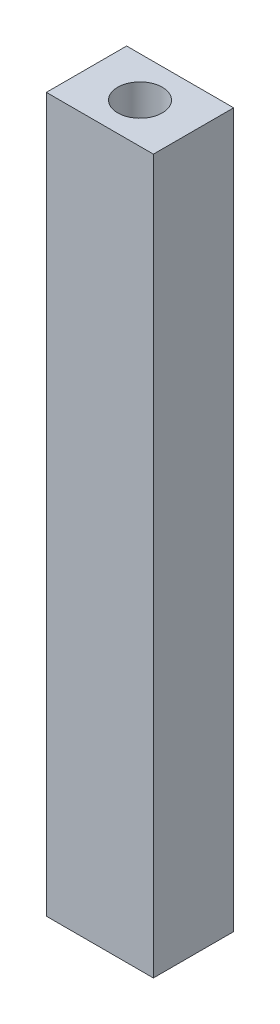
SolidWorks part; units mm, degrees
ref_plane "前视基准面" through (0, 0, 0) normal (0, 0, 1) x (1, 0, 0)
ref_plane "上视基准面" through (0, 0, 0) normal (0, 1, 0) x (1, 0, 0)
ref_plane "右视基准面" through (0, 0, 0) normal (1, 0, 0) x (0, 0, -1)
other "Configuration Table"
sketch "草图2" plane through (0, 0, 0) normal (0, 1, 0) x (1, 0, 0)
  line L1 (-6, -4.5) -> (6, -4.5)
  line L2 (-6, -4.5) -> (-6, 4.5)
  line L3 (-6, 4.5) -> (6, 4.5)
  line L4 (6, -4.5) -> (6, 4.5)
  line L5 (-6, -4.5) -> (6, 4.5) construction
  line L6 (-6, 4.5) -> (6, -4.5) construction
  point P0 (0, 0)
  dimension "D1" = 12
  dimension "D2" = 9
extrude "凸台-拉伸1" add sketch "草图2" along normal blind 80
sketch "草图3" plane through (0, 0, 0) normal (0, -1, 0) x (1, 0, 0)
  circle A0 centre (0, 0) radius 3
  dimension "D1" = 6
extrude "切除-拉伸1" cut sketch "草图3" against normal blind 15
sketch "草图4" plane through (0, 80, 0) normal (0, 1, 0) x (1, 0, 0)
  circle A0 centre (0, 0) radius 2.5
  point P3 (0, 0)
  dimension "D1" = 5
extrude "切除-拉伸2" cut sketch "草图4" against normal blind 15
